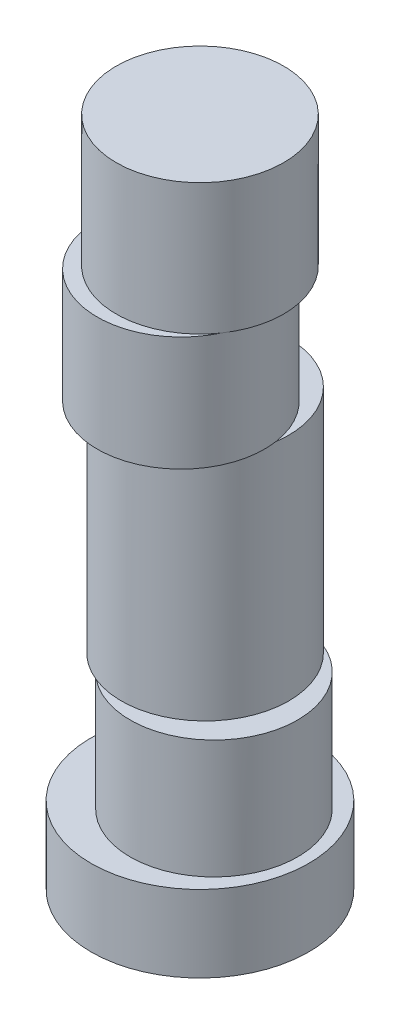
SolidWorks part; units mm, degrees
ref_plane "Front Plane" through (0, 0, 0) normal (0, 0, 1) x (1, 0, 0)
ref_plane "Top Plane" through (0, 0, 0) normal (0, 1, 0) x (1, 0, 0)
ref_plane "Right Plane" through (0, 0, 0) normal (1, 0, 0) x (0, 0, -1)
sketch "Sketch1" plane through (0, 0, 0) normal (0, 1, 0) x (1, 0, 0)
  circle A0 centre (0, 0) radius 7.8
  dimension "D1" = 15.6
extrude "Boss-Extrude1" add sketch "Sketch1" along normal blind 5.5
sketch "Sketch2" plane through (0, 5.5, 0) normal (0, 1, 0) x (1, 0, 0)
  line L0 (0, 0) -> (1, 0) construction
  circle A0 centre (1, 0) radius 6
  dimension "D2" = 12
extrude "Boss-Extrude2" add sketch "Sketch2" along normal blind 8.5
sketch "Sketch4" plane through (0, 14, 0) normal (0, 1, 0) x (1, 0, 0)
  line L0 (0, 0) -> (1, 0) construction
  line L1 (0, 0) -> (-0.5, 0.866) construction
  circle A0 centre (-0.5, 0.866) radius 6
  dimension "D4" = 12
  dimension "D1" = 120
  dimension "D2" = 1
  dimension "D3" = 1
extrude "Boss-Extrude3" add sketch "Sketch4" along normal blind 16.5
sketch "Sketch7" plane through (0, 30.5, 0) normal (0, 1, 0) x (1, 0, 0)
  line L0 (0, 0) -> (-0.5, 0.866) construction
  line L1 (0, 0) -> (0, 1) construction
  line L2 (0, 0) -> (-0.5, -0.866) construction
  circle A0 centre (-0.5, -0.866) radius 6
  dimension "D6" = 12
  dimension "D1" = 1
  dimension "D2" = 1
  dimension "D3" = 30
  dimension "D4" = 120
  dimension "D5" = 1
extrude "Boss-Extrude4" add sketch "Sketch7" along normal blind 8.2
sketch "Sketch3" plane through (0, 0, 0) normal (0, -1, 0) x (1, 0, 0)
  circle A0 centre (0, 0) radius 4
  dimension "D1" = 8
extrude "Cut-Extrude2" cut sketch "Sketch3" against normal through all
sketch "Sketch8" plane through (0, 38.7, 0) normal (0, 1, 0) x (1, 0, 0)
  circle A0 centre (0, 0) radius 4 construction
  circle A1 centre (0, 0) radius 4 construction
  circle A2 centre (0, 0) radius 6
  dimension "D1" = 12
extrude "Boss-Extrude5" add sketch "Sketch8" along normal blind 9.4
